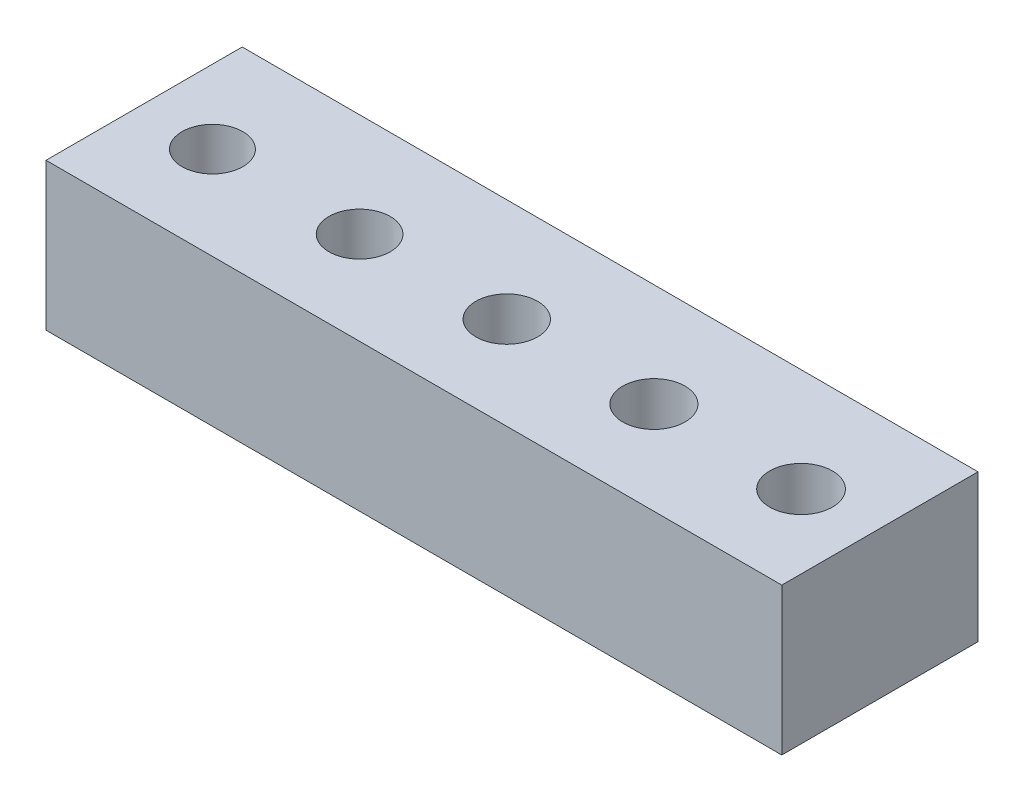
SolidWorks part; units mm, degrees
ref_plane "Front Plane" through (0, 0, 0) normal (0, 0, 1) x (1, 0, 0)
ref_plane "Top Plane" through (0, 0, 0) normal (0, 1, 0) x (1, 0, 0)
ref_plane "Right Plane" through (0, 0, 0) normal (1, 0, 0) x (0, 0, -1)
sketch "Sketch3" plane through (0, 0, 0) normal (0, 1, 0) x (1, 0, 0)
  line L1 (0, 0) -> (38.1, 0)
  line L2 (0, 0) -> (0, 10.16)
  line L3 (0, 10.16) -> (38.1, 10.16)
  line L4 (38.1, 0) -> (38.1, 10.16)
  point P4 (0, 0)
  dimension "D1" = 10.16
  dimension "D2" = 38.1
extrude "Boss-Extrude2" add sketch "Sketch3" along normal blind 7.62
sketch "Sketch1" plane through (0, 0, 0) normal (0, 1, 0) x (1, 0, 0)
  line L0 (0, 4.8073) -> (38.1, 4.8073) construction
  line L1 (0, 0) -> (38.1, 0)
  line L2 (0, 0) -> (0, 10.16)
  line L3 (0, 10.16) -> (38.1, 10.16)
  line L4 (38.1, 0) -> (38.1, 10.16)
  circle A0 centre (3.81, 4.8073) radius 1.5748
  circle A1 centre (11.43, 4.8073) radius 1.5875
  circle A2 centre (19.05, 4.8073) radius 1.6002
  circle A3 centre (26.67, 4.8073) radius 1.6129
  circle A4 centre (34.29, 4.8073) radius 1.6256
  dimension "D2" = 3.1496
  dimension "D3" = 3.175
  dimension "D4" = 3.2004
  dimension "D5" = 3.2258
  dimension "D6" = 3.2512
  dimension "D1" = 10.16
  dimension "D7" = 3.81
  dimension "D8" = 11.43
  dimension "D9" = 19.05
  dimension "D10" = 26.67
  dimension "D11" = 34.29
  dimension "D12" = 38.1
extrude "Cut-Extrude1" cut sketch "Sketch1" against normal blind 4.7498 from surface at 7.62 contours A0 | A1 | A4 | A3 | A2 starting at face at (19.05, 7.62, -5.08)
